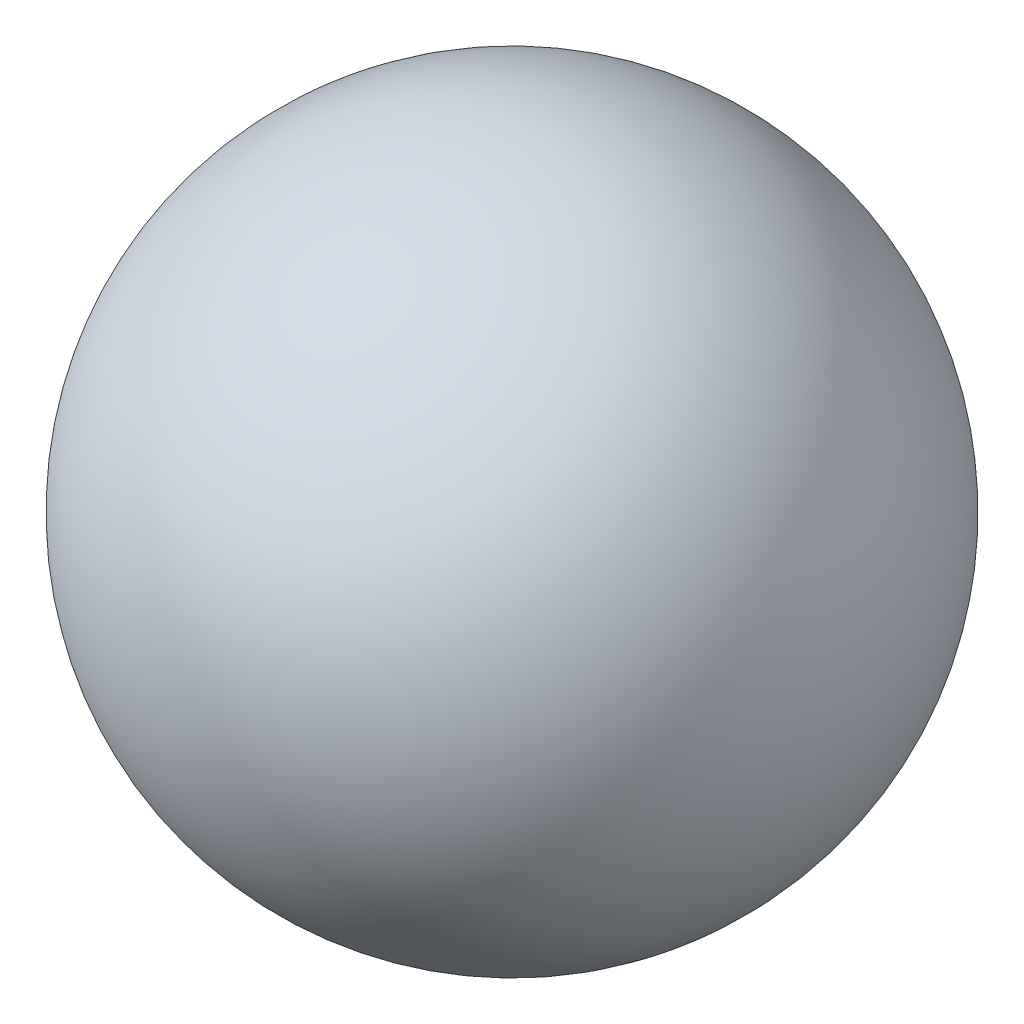
SolidWorks part; units mm, degrees
ref_plane "Front Plane" through (0, 0, 0) normal (0, 0, 1) x (1, 0, 0)
ref_plane "Top Plane" through (0, 0, 0) normal (0, 1, 0) x (1, 0, 0)
ref_plane "Right Plane" through (0, 0, 0) normal (1, 0, 0) x (0, 0, -1)
sketch "Sketch1" plane through (0, 0, 0) normal (0, 0, 1) x (1, 0, 0)
  line L0 (1.605, -2.7799) -> (2.3638, -4.0941)
  line L1 (1.8455, -3.1965) -> (2.1741, -3.7656) construction
  arc A0 (2.3638, -4.0941) -> (1.605, -2.7799) centre (1.9844, -3.437) ccw
revolve "Revolve1" add sketch "Sketch1" angle 360 about L1
